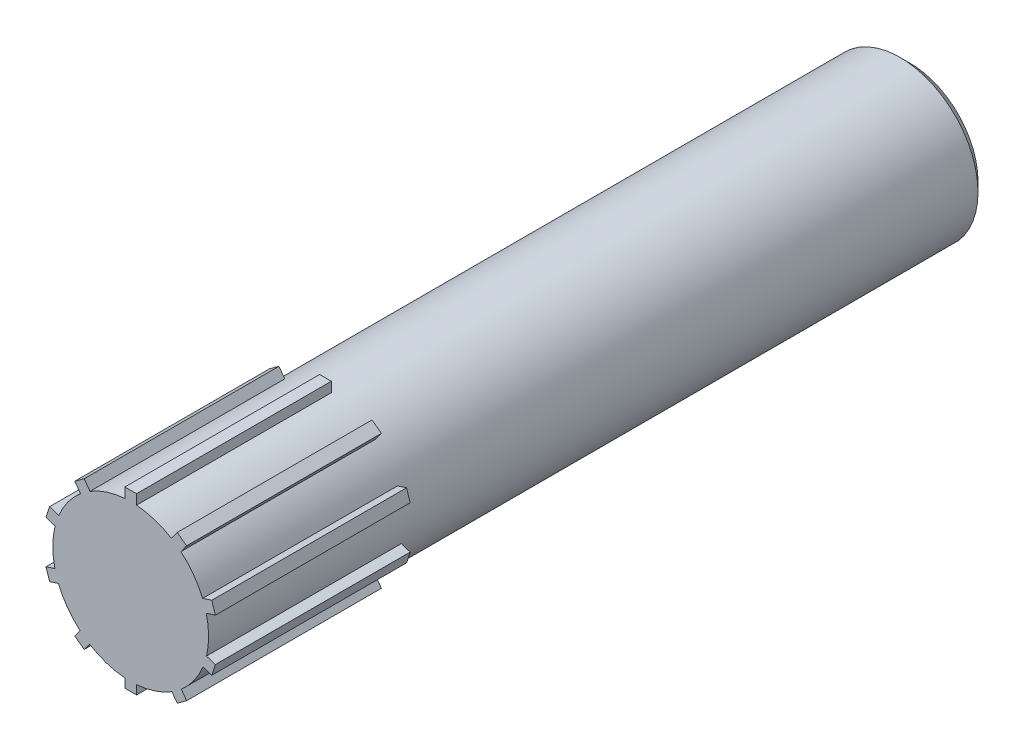
SolidWorks part; units mm, degrees
ref_plane "Front" through (0, 0, 0) normal (0, 0, 1) x (1, 0, 0)
ref_plane "Top" through (0, 0, 0) normal (0, 1, 0) x (1, 0, 0)
ref_plane "Right" through (0, 0, 0) normal (1, 0, 0) x (0, 0, -1)
sketch "Sketch1" plane through (0, 0, 0) normal (0, 0, 1) x (1, 0, 0)
  circle A0 centre (0, 0) radius 4
  dimension "D1" = 8
extrude "Boss-Extrude1" add sketch "Sketch1" along normal blind 40
sketch "Sketch8" plane through (0, 0, 0) normal (0, 1, 0) x (1, 0, 0)
  line L0 (0, 0) -> (0, -40) construction
  line L1 (-4, -40) -> (4, -40) construction
  line L2 (0, -5) -> (0, -9) construction
  line L3 (1.5, -5) -> (1.5, -9)
  line L4 (-1.5, -5) -> (-1.5, -9)
  arc A0 (1.5, -5) -> (-1.5, -5) centre (0, -5) ccw
  arc A1 (-1.5, -9) -> (1.5, -9) centre (0, -9) ccw
  point P7 (0, -7)
  point P12 (0, 0)
  dimension "D2" = 1.5
  dimension "D1" = 4
  dimension "D3" = 5
extrude "Cut-Extrude2" cut sketch "Sketch8" against normal through all from offset 2.5 offset against normal yes
sketch "Sketch9" plane through (0, 0, 40) normal (0, 0, 1) x (1, 0, 0)
  line L0 (0, 0) -> (0, 5.1775) construction
  line L2 (-0.3, 4.5) -> (0.3, 4.5)
  line L3 (-0.3, 4.5) -> (-0.3, 1.6286)
  line L4 (-0.3, 1.6286) -> (0.3, 1.6286)
  line L5 (0.3, 4.5) -> (0.3, 1.6286)
  point P6 (-0.4317, 4.6522)
  dimension "D1" = 0.6
  dimension "D2" = 4.5
extrude "Boss-Extrude2" add sketch "Sketch9" against normal blind 10
pattern_circular "CirPattern1" count 10 over 360 about axis through (0, 0.0254, 0) along (0, 0, 1) of "Boss-Extrude2"
chamfer "Chamfer1" distance 0.5 angle 45 1 edges at (4, 0, 0)
